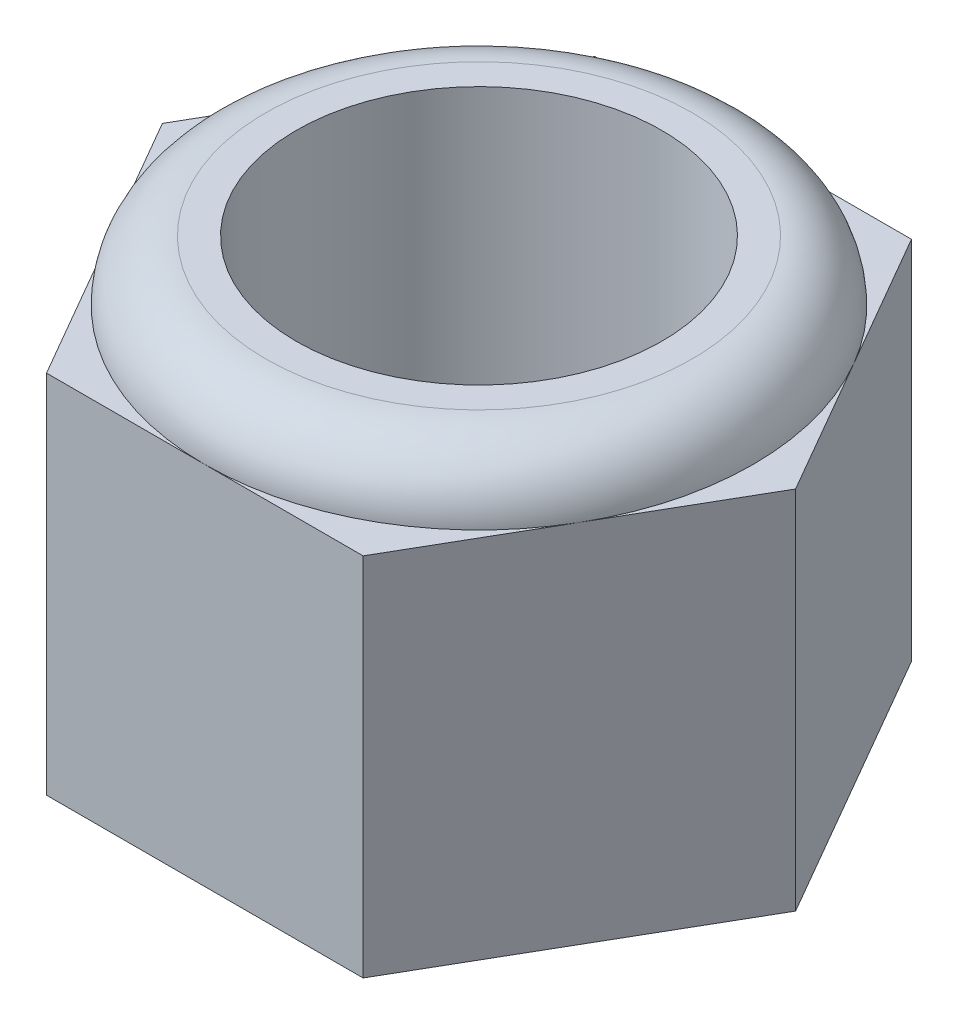
SolidWorks part; units mm, degrees
material "Acier allié"
ref_plane "Face" through (0, 0, 0) normal (0, 0, 1) x (1, 0, 0)
ref_plane "Dessus" through (0, 0, 0) normal (0, 1, 0) x (1, 0, 0)
ref_plane "Droite" through (0, 0, 0) normal (1, 0, 0) x (0, 0, -1)
sketch "Esquisse1" plane through (0, 0, 0) normal (0, 1, 0) x (1, 0, 0)
  line L1 (8.2489, 14.2875) -> (-8.2489, 14.2875)
  line L2 (-8.2489, 14.2875) -> (-16.4978, 0)
  line L3 (-16.4978, 0) -> (-8.2489, -14.2875)
  line L4 (-8.2489, -14.2875) -> (8.2489, -14.2875)
  line L5 (8.2489, -14.2875) -> (16.4978, 0)
  line L6 (16.4978, 0) -> (8.2489, 14.2875)
  circle A0 centre (0, 0) radius 14.2875 construction
  dimension "D1" = 28.575
extrude "Boss.-Extru.1" add sketch "Esquisse1" along normal blind 22.225
sketch "Esquisse2" plane through (0, 22.225, 0) normal (0, 1, 0) x (1, 0, 0)
  circle A0 centre (0, 0) radius 9.525
  dimension "D1" = 19.05
extrude "Enlèv. mat.-Extru.1" cut sketch "Esquisse2" against normal through all
cosmetic thread "Représentation de filetage1" parameters "D2"=19.0754
sketch "Esquisse3" plane through (0, 0, 0) normal (1, 0, 0) x (0, 0, -1)
  line L0 (-9.525, 22.225) -> (-11.1125, 22.225) construction
  line L1 (-14.2875, 22.225) -> (0, 22.225) construction
  line L2 (-14.2875, 22.225) -> (-14.2875, 0) construction
  line L5 (-14.2875, 22.225) -> (-12.7, 22.225)
  line L6 (-12.7, 22.225) -> (-11.1125, 22.225)
  line L7 (-14.2875, 19.05) -> (-17.4625, 19.05)
  line L8 (-17.4625, 19.05) -> (-17.4625, 22.225)
  line L9 (-17.4625, 22.225) -> (-14.2875, 22.225)
  line L10 (0, 0) -> (0, 22.225) construction
  arc A0 (-11.1125, 22.225) -> (-14.2875, 19.05) centre (-11.1125, 19.05) ccw
revolve "Enlèvement de matière-Révolution1" cut sketch "Esquisse3" angle 360 about L10
equation "\"W\"=1.125"
equation "\"D1@Esquisse1\"=\"W\""
equation "\"H\"=7/8"
equation "\"D1@Boss.-Extru.1\"=\"H\""
equation "\"D\"=3/4"
equation "\"D1@Esquisse2\"=\"D\""
equation "\"D2@Représentation de filetage1\"=\"D\"+0.001"
